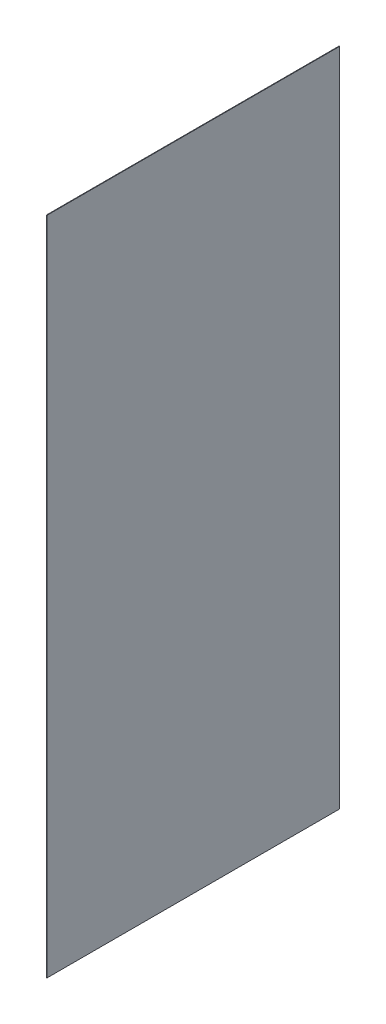
SolidWorks part; units mm, degrees
ref_plane "Front Plane" through (0, 0, 0) normal (0, 0, 1) x (1, 0, 0)
ref_plane "Top Plane" through (0, 0, 0) normal (0, 1, 0) x (1, 0, 0)
ref_plane "Right Plane" through (0, 0, 0) normal (1, 0, 0) x (0, 0, -1)
other "Configuration Table"
sketch "Sketch1" plane through (0, 0, 0) normal (0, 0, 1) x (1, 0, 0)
  line L1 (0, 120) -> (1.5, 120)
  line L2 (0, 120) -> (0, 1970)
  line L3 (0, 1970) -> (1.5, 1970)
  line L4 (1.5, 120) -> (1.5, 1970)
extrude "STORE_dis_yan_sol_1" add sketch "Sketch1" against normal blind 820 separate body
